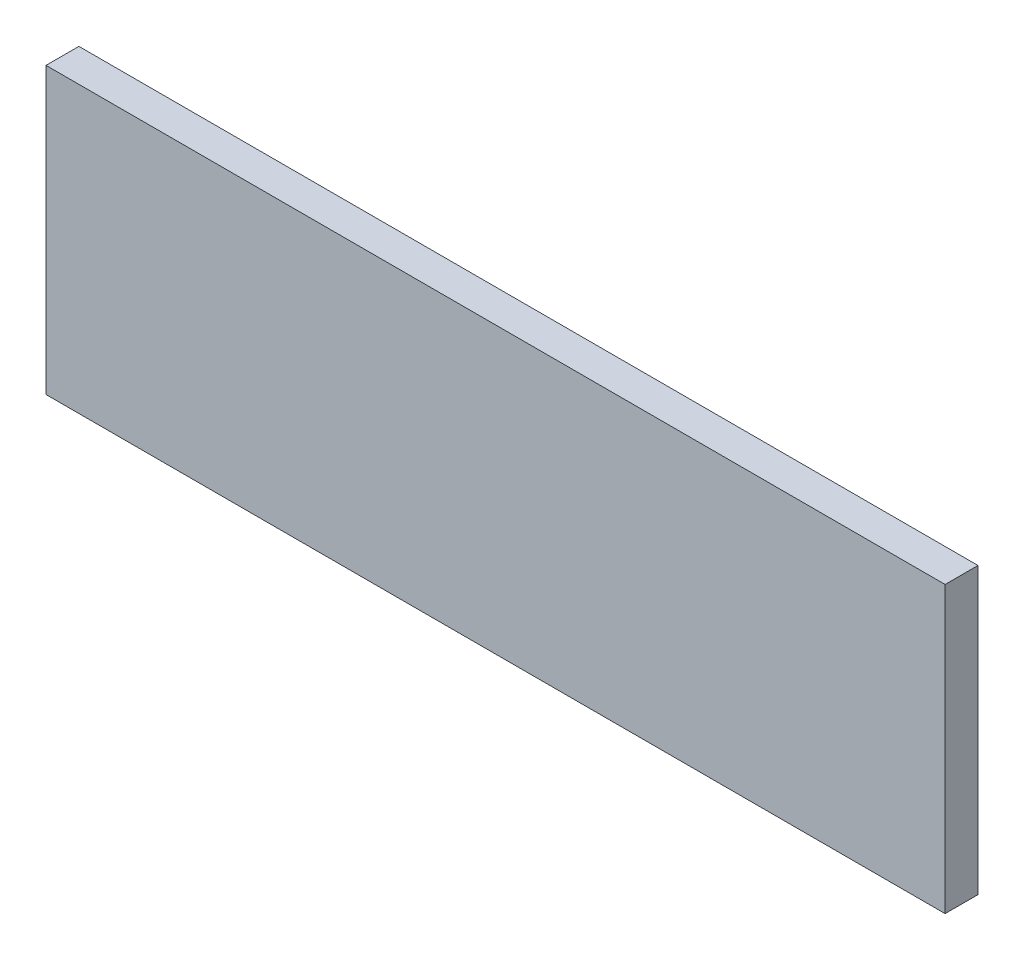
SolidWorks part; units mm, degrees
ref_plane "前视基准面" through (0, 0, 0) normal (0, 0, 1) x (1, 0, 0)
ref_plane "上视基准面" through (0, 0, 0) normal (0, 1, 0) x (1, 0, 0)
ref_plane "右视基准面" through (0, 0, 0) normal (1, 0, 0) x (0, 0, -1)
other "Configuration Table"
sketch "草图1" plane through (0, 0, 0) normal (0, 0, 1) x (1, 0, 0)
  line L0 (0, 0) -> (82, 0)
  line L1 (82, 0) -> (82, 26)
  line L2 (82, 26) -> (0, 26)
  line L3 (0, 26) -> (0, 0)
  dimension "width" = 82
  dimension "height" = 26
extrude "Stereo_Tray" add sketch "草图1" along normal blind 3
